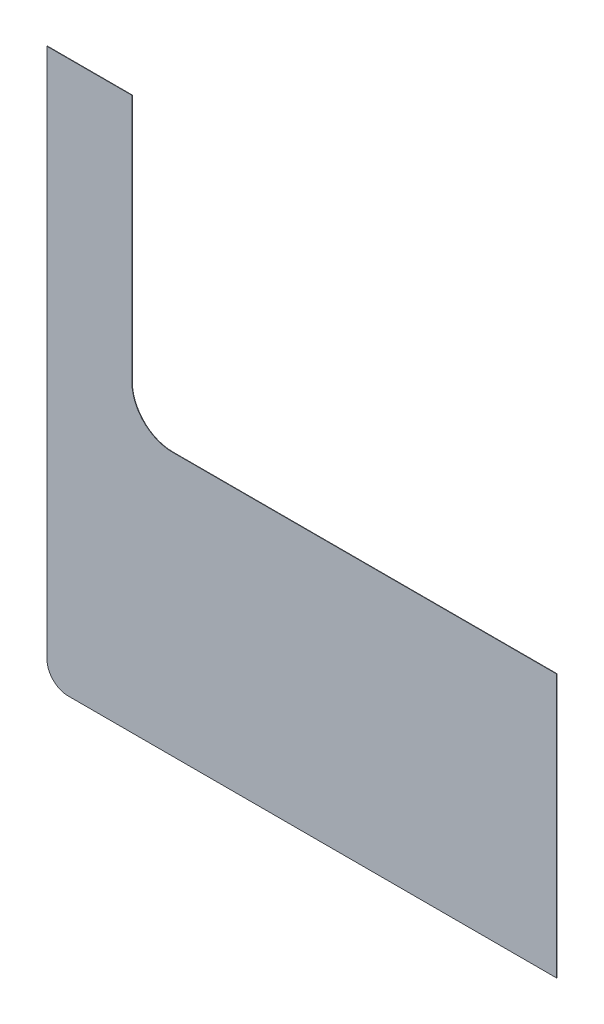
SolidWorks part; units mm, degrees
ref_plane "前视基准面" through (0, 0, 0) normal (0, 0, 1) x (1, 0, 0)
ref_plane "上视基准面" through (0, 0, 0) normal (0, 1, 0) x (1, 0, 0)
ref_plane "右视基准面" through (0, 0, 0) normal (1, 0, 0) x (0, 0, -1)
sketch "草图1" plane through (0, 0, 0) normal (0, 0, 1) x (1, 0, 0)
  line L0 (0, 0) -> (-120, 0)
  line L1 (-120, 0) -> (-120, 130)
  line L2 (-120, 130) -> (-100, 130)
  line L3 (-100, 130) -> (-100, 62)
  line L4 (-100, 62) -> (0, 62)
  line L5 (0, 62) -> (0, 0)
  dimension "D1" = 130
  dimension "D2" = 120
  dimension "D3" = 20
  dimension "D4" = 62
extrude "凸台-拉伸1" add sketch "草图1" along normal blind 0.1
fillet "圆角1" radius 9.5 1 edges at (-100, 62, 0.05)
fillet "圆角2" radius 5 1 edges at (-120, 0, 0.05)
sketch3d "3D草图1" [suppressed]
  line L0 (-11.5, 30, 0.5) -> (-11.5, 100, 0.5) construction
  arc A0 (-1.5, 20, 0.5) -> (-11.5, 30, 0.5) centre (-1.5, 30, 0.5) ccw construction
  point P0 (-1.5, 20, 0.5)
  point P1 (-8.5711, 22.9289, 0.5)
  point P3 (-11.5, 30, 0.5)
  point P7 (-1.5, 30, -9.5)
  point P8 (-11.5, 49.1552, 0.5)
  point P10 (-11.5, 87.2694, 0.5)
